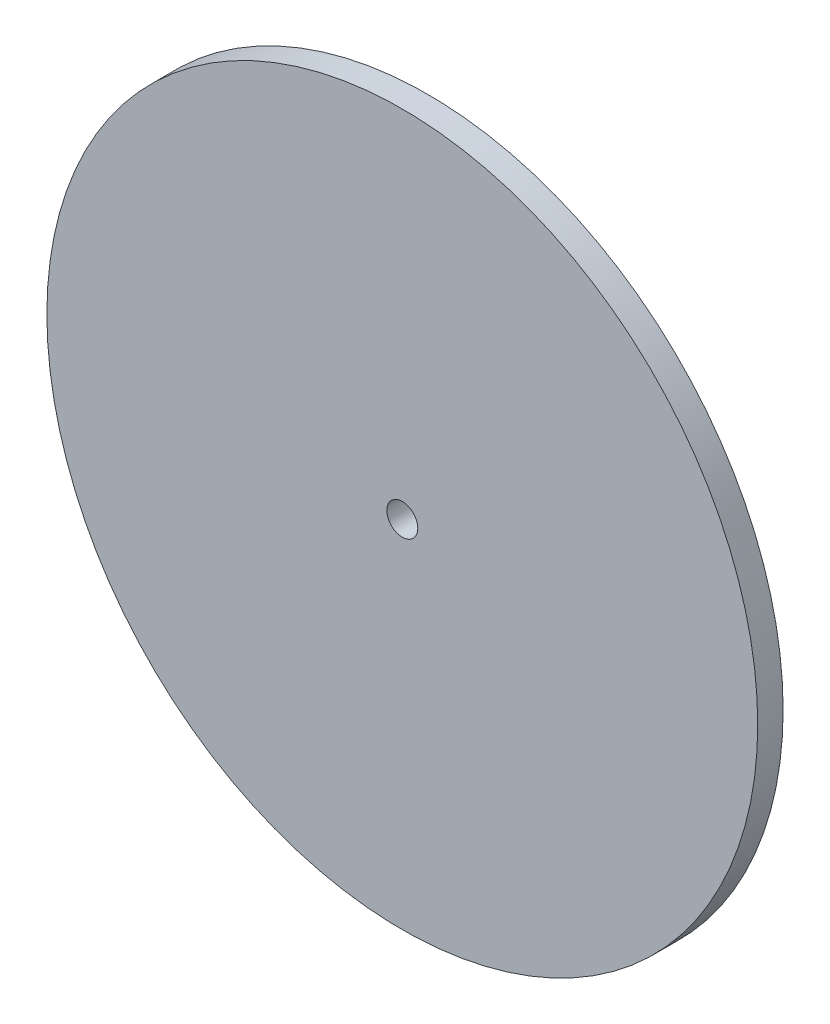
SolidWorks part; units mm, degrees
material "Balsa"
ref_plane "Front Plane" through (0, 0, 0) normal (0, 0, 1) x (1, 0, 0)
ref_plane "Top Plane" through (0, 0, 0) normal (0, 1, 0) x (1, 0, 0)
ref_plane "Right Plane" through (0, 0, 0) normal (1, 0, 0) x (0, 0, -1)
sketch "Sketch1" plane through (0, 0, 0) normal (0, 0, 1) x (1, 0, 0)
  circle A1 centre (0, 0) radius 70
  circle A2 centre (0, 0) radius 3.05
  dimension "D1" = 140
  dimension "D2" = 6.1
extrude "Boss-Extrude1" add sketch "Sketch1" along normal blind 5
